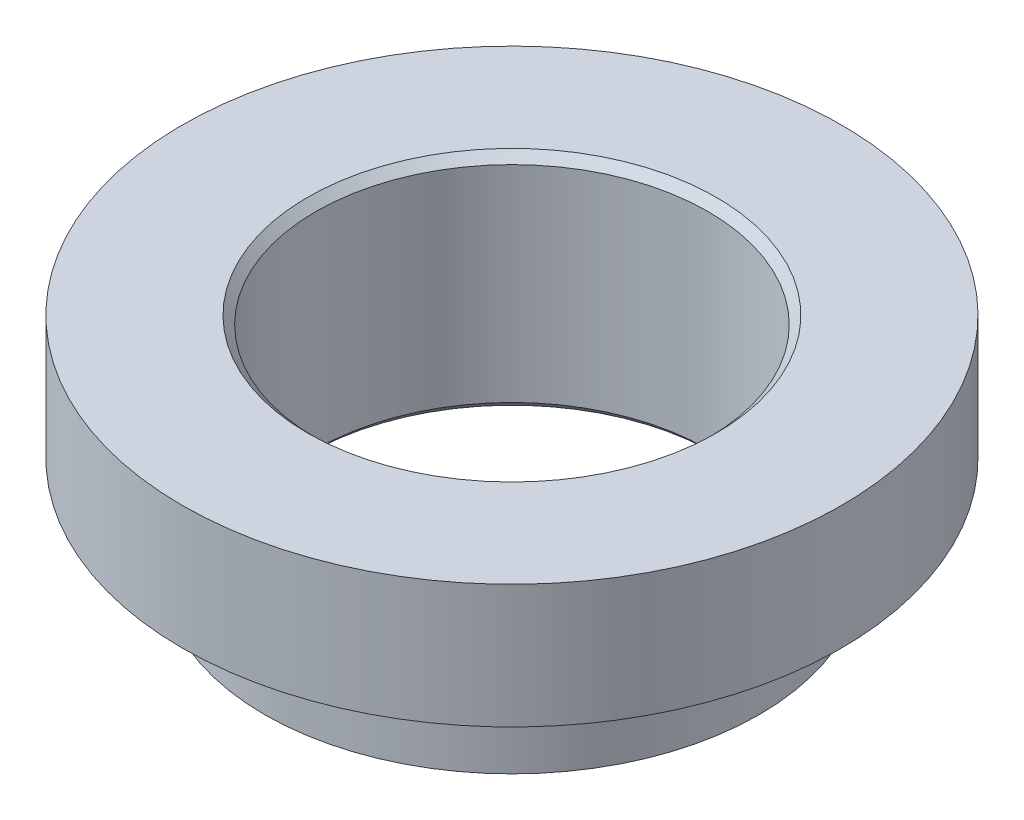
SolidWorks part; units mm, degrees
ref_plane "Plan de face" through (0, 0, 0) normal (0, 0, 1) x (1, 0, 0)
ref_plane "Plan de dessus" through (0, 0, 0) normal (0, 1, 0) x (1, 0, 0)
ref_plane "Plan de droite" through (0, 0, 0) normal (1, 0, 0) x (0, 0, -1)
sketch "Esquisse1" plane through (0, 0, 0) normal (0, 0, 1) x (1, 0, 0)
  line L0 (0, 0) -> (0, -60.2875) construction
  line L1 (-12.4, 0) -> (-20, 0)
  line L2 (-20, 0) -> (-20, -7.5)
  line L3 (-20, -7.5) -> (-15, -7.5)
  line L4 (-15, -7.5) -> (-15, -13.5)
  line L5 (-15, -13.5) -> (-12.4, -13.5)
  line L6 (-11.9, -0.5) -> (-11.9, -13)
  line L7 (-12.4, 0) -> (-11.9, -0.5)
  line L8 (-11.9, -13) -> (-12.4, -13.5)
  point P3 (-11.9, 0)
  point P9 (-11.9, -13.5)
  dimension "D1" = 40
  dimension "D2" = 23.8
  dimension "D3" = 30
  dimension "D4" = 13.5
  dimension "D5" = 6
revolve "Révolution1" add sketch "Esquisse1" angle 360 about L0
